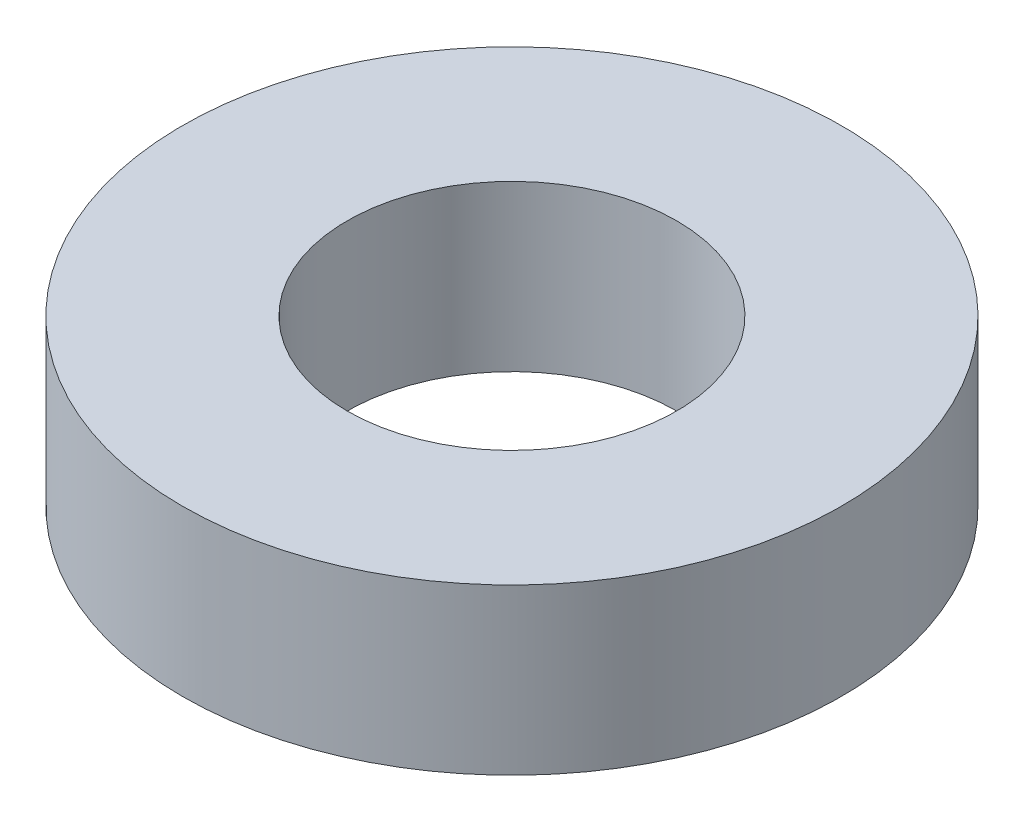
SolidWorks part; units mm, degrees
ref_plane "前视基准面" through (0, 0, 0) normal (0, 0, 1) x (1, 0, 0)
ref_plane "上视基准面" through (0, 0, 0) normal (0, 1, 0) x (1, 0, 0)
ref_plane "右视基准面" through (0, 0, 0) normal (1, 0, 0) x (0, 0, -1)
sketch "草图1" plane through (0, 0, 0) normal (0, 1, 0) x (1, 0, 0)
  circle A0 centre (0, 0) radius 10
  circle A1 centre (0, 0) radius 20
extrude "凸台-拉伸1" add sketch "草图1" along normal blind 10
